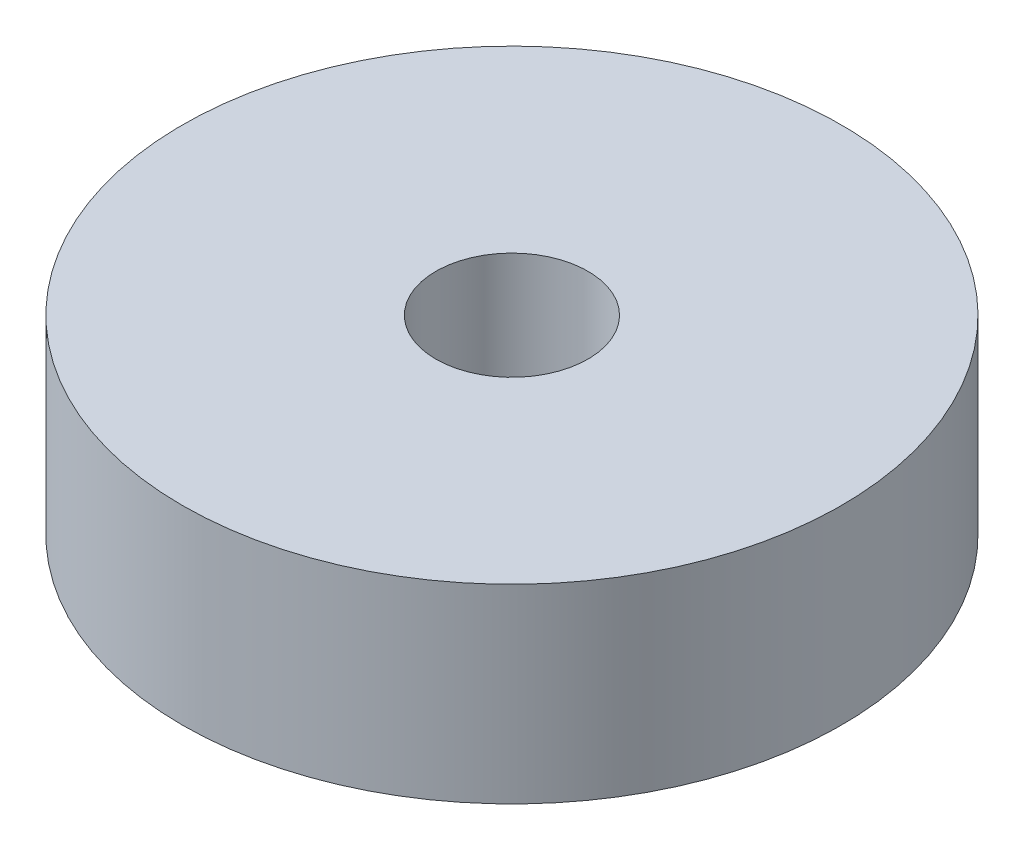
SolidWorks part; units mm, degrees
material "Pine"
ref_plane "Front Plane" through (0, 0, 0) normal (0, 0, 1) x (1, 0, 0)
ref_plane "Top Plane" through (0, 0, 0) normal (0, 1, 0) x (1, 0, 0)
ref_plane "Right Plane" through (0, 0, 0) normal (1, 0, 0) x (0, 0, -1)
sketch "Sketch1" plane through (0, 0, 0) normal (0, 1, 0) x (1, 0, 0)
  circle A0 centre (0, 0) radius 11
  circle A1 centre (0, 0) radius 2.54
  dimension "D1" = 22
  dimension "D2" = 5.08
extrude "Boss-Extrude1" add sketch "Sketch1" along normal blind 6.35
